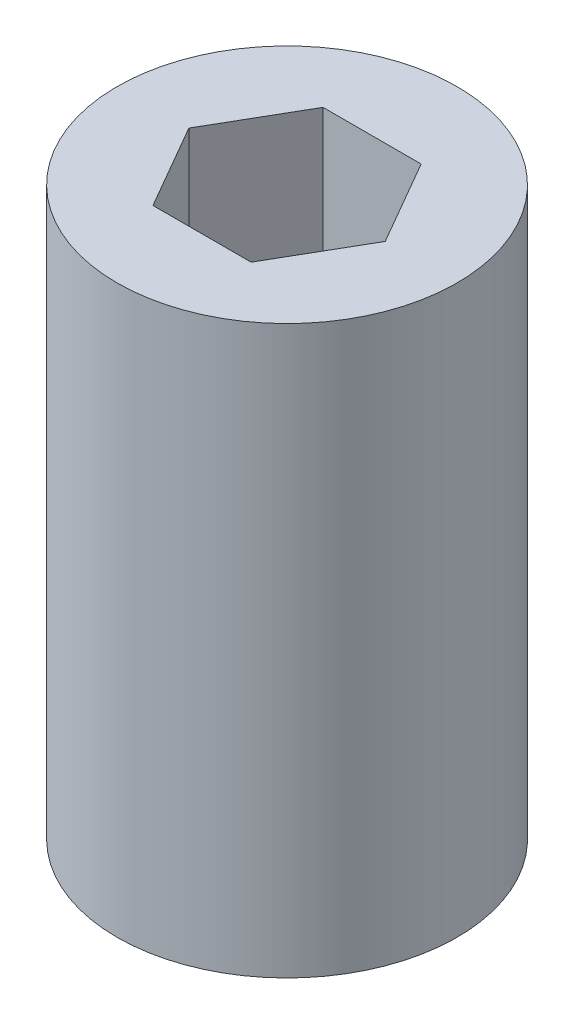
SolidWorks part; units mm, degrees
material "AISI 304"
ref_plane "Front Plane" through (0, 0, 0) normal (0, 0, 1) x (1, 0, 0)
ref_plane "Top Plane" through (0, 0, 0) normal (0, 1, 0) x (1, 0, 0)
ref_plane "Right Plane" through (0, 0, 0) normal (1, 0, 0) x (0, 0, -1)
sketch "Sketch1" plane through (0, 0, 0) normal (0, 0, 1) x (1, 0, 0)
  line L0 (0, 61.6916) -> (0, -59.3578) construction
  line L1 (0, -5) -> (1.5, -5)
  line L2 (1.5, -5) -> (1.5, 0)
  line L3 (1.5, 0) -> (0, 0)
  line L6 (0, 0) -> (0, -5)
  dimension "L" = 5
  dimension "M" = 3
revolve "Revolve1" add sketch "Sketch1" angle 360 about L0
cosmetic thread "Cosmetic Thread1" parameters "D2"=2.5
sketch "Sketch2" plane through (0, 0, 0) normal (0, 1, 0) x (-1, 0, 0)
  line L1 (-0.433, -0.75) -> (0.433, -0.75)
  line L2 (0.433, -0.75) -> (0.866, 0)
  line L3 (0.866, 0) -> (0.433, 0.75)
  line L4 (0.433, 0.75) -> (-0.433, 0.75)
  line L5 (-0.433, 0.75) -> (-0.866, 0)
  line L6 (-0.866, 0) -> (-0.433, -0.75)
  circle A0 centre (0, 0) radius 0.75 construction
  dimension "B" = 1.5
sketch "Sketch3" plane through (0, -5, 0) normal (0, -1, 0) x (1, 0, 0)
  circle A0 centre (0, 0) radius 0.75
  dimension "d" = 1.5
extrude "Boss-Extrude1" add sketch "Sketch3" along normal blind 0.5 separate body
extrude "Cut-Extrude1" cut sketch "Sketch2" against normal blind 2
